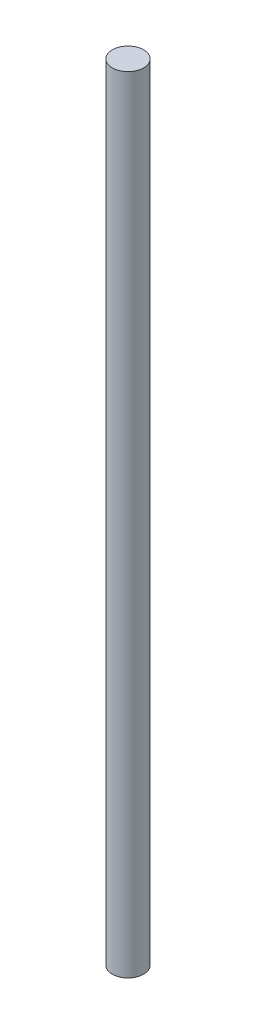
SolidWorks part; units mm, degrees
ref_plane "前视基准面" through (0, 0, 0) normal (0, 0, 1) x (1, 0, 0)
ref_plane "上视基准面" through (0, 0, 0) normal (0, 1, 0) x (1, 0, 0)
ref_plane "右视基准面" through (0, 0, 0) normal (1, 0, 0) x (0, 0, -1)
sketch "草图1" plane through (0, 0, 0) normal (0, 1, 0) x (1, 0, 0)
  circle A0 centre (0, 0) radius 3
  dimension "D1" = 6
extrude "凸台-拉伸1" add sketch "草图1" along normal mid plane 150
